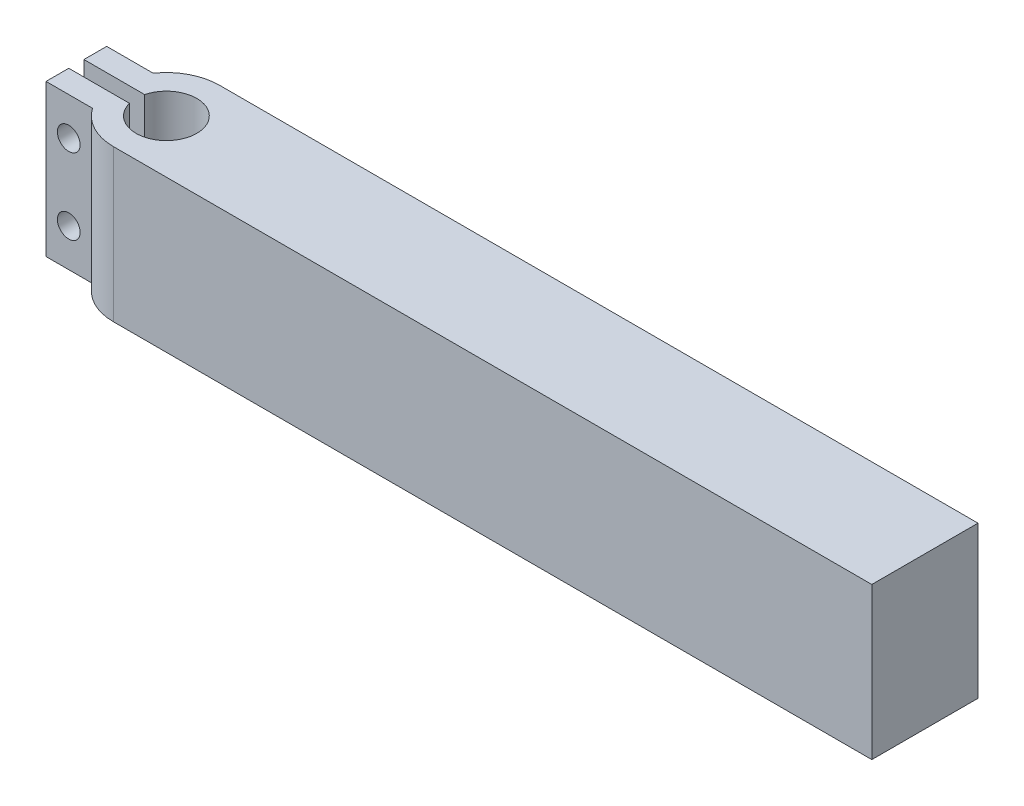
SolidWorks part; units mm, degrees
ref_plane "Plano frontal" through (0, 0, 0) normal (0, 0, 1) x (1, 0, 0)
ref_plane "Plano superior" through (0, 0, 0) normal (0, 1, 0) x (1, 0, 0)
ref_plane "Plano direito" through (0, 0, 0) normal (1, 0, 0) x (0, 0, -1)
sketch "Esboço1" plane through (0, 0, 0) normal (0, 1, 0) x (1, 0, 0)
  line L0 (-2.5769, 7) -> (108.0096, 7) construction
  line L1 (0, 0) -> (100, 0)
  line L2 (0, 0) -> (0, 14)
  line L3 (0, 14) -> (100, 14)
  line L4 (100, 0) -> (100, 14)
  circle A0 centre (0, 7) radius 7
  point P9 (108.0096, 8)
  dimension "D1" = 14
  dimension "D2" = 7
  dimension "D3" = 100
extrude "Ressalto-extrusão1" add sketch "Esboço1" along normal blind 20
sketch "Esboço2" plane through (0, 20, 0) normal (0, 1, 0) x (1, 0, 0)
  circle A0 centre (0, 7) radius 4
  dimension "D1" = 8
extrude "Corte-extrusão1" cut sketch "Esboço2" against normal blind 20
sketch "Esboço3" plane through (0, 20, 0) normal (0, 1, 0) x (1, 0, 0)
  line L1 (-9, 8) -> (1, 8)
  line L2 (-9, 8) -> (-9, 6)
  line L3 (-9, 6) -> (1, 6)
  line L4 (1, 8) -> (1, 6)
  line L5 (-9, 8) -> (1, 6) construction
  line L6 (-9, 6) -> (1, 8) construction
  circle A0 centre (0, 7) radius 4 construction
  point P0 (-4, 7)
  dimension "D1" = 10
  dimension "D2" = 2
extrude "Corte-extrusão2" cut sketch "Esboço3" against normal blind 20
sketch "Esboço4" plane through (0, 20, 0) normal (0, 1, 0) x (1, 0, 0)
  line L1 (-3.873, 8) -> (-11.873, 8)
  line L2 (-3.873, 8) -> (-3.873, 11)
  line L3 (-3.873, 11) -> (-11.873, 11)
  line L4 (-11.873, 8) -> (-11.873, 11)
  line L5 (-3.873, 6) -> (-11.873, 6)
  line L6 (-3.873, 6) -> (-3.873, 3)
  line L7 (-3.873, 3) -> (-11.873, 3)
  line L8 (-11.873, 6) -> (-11.873, 3)
  dimension "D1" = 3
  dimension "D2" = 3
  dimension "D3" = 8
  dimension "D4" = 8
extrude "Ressalto-extrusão2" add sketch "Esboço4" against normal blind 20
sketch "Esboço5" plane through (0, 0, -3) normal (0, 0, 1) x (1, 0, 0)
  line L0 (-8.873, 20.1847) -> (-8.873, -3.1303) construction
  line L1 (-11.873, 0) -> (-5.7446, 0) construction
  line L2 (-3.873, 20) -> (-11.873, 20) construction
  line L3 (-11.873, 0) -> (-11.873, 20) construction
  circle A0 centre (-8.873, 15) radius 1.5
  circle A1 centre (-8.873, 5) radius 1.5
  dimension "D1" = 3
  dimension "D2" = 3
  dimension "D3" = 5
  dimension "D4" = 5
  dimension "D5" = 3
extrude "Corte-extrusão3" cut sketch "Esboço5" against normal blind 20
